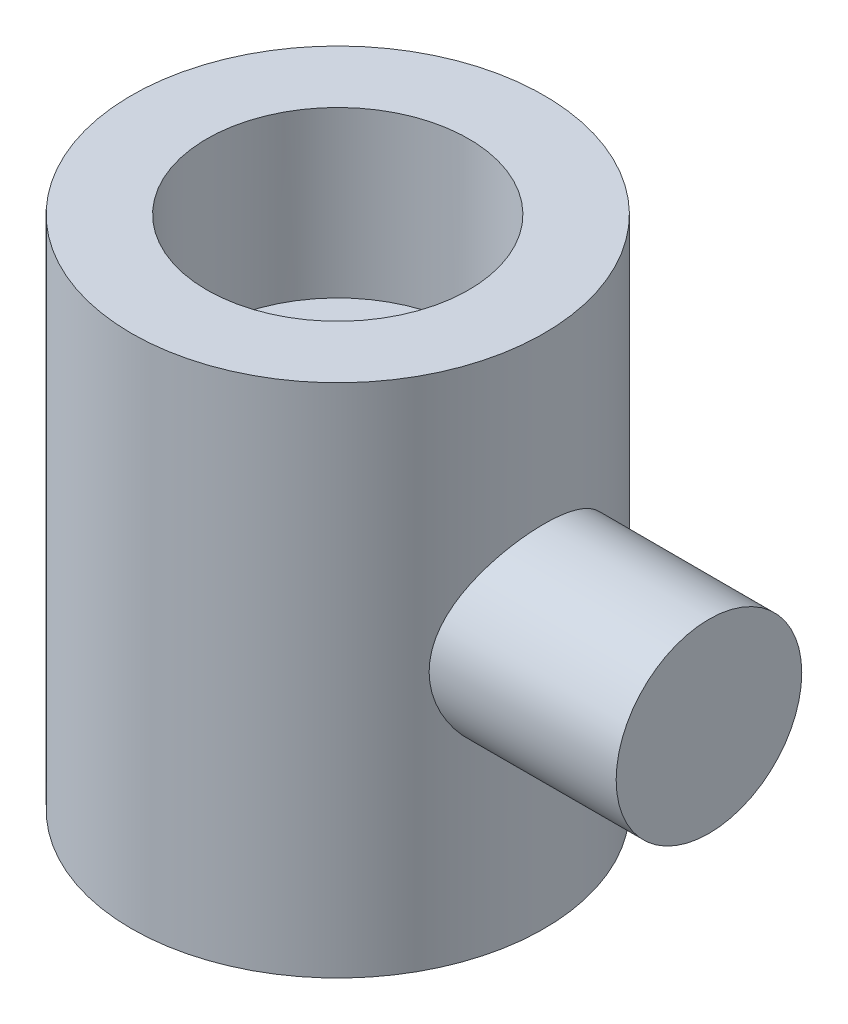
SolidWorks part; units mm, degrees
ref_plane "Front Plane" through (0, 0, 0) normal (0, 0, 1) x (1, 0, 0)
ref_plane "Top Plane" through (0, 0, 0) normal (0, 1, 0) x (1, 0, 0)
ref_plane "Right Plane" through (0, 0, 0) normal (1, 0, 0) x (0, 0, -1)
sketch "Sketch2" plane through (0, 0, 0) normal (0, 1, 0) x (1, 0, 0)
  circle A1 centre (0, 0) radius 10
  dimension "D2" = 20
extrude "Boss-Extrude1" add sketch "Sketch2" along normal blind 25
sketch "Sketch3" plane through (0, 0, 0) normal (1, 0, 0) x (0, 0, -1)
  line L0 (10, 25) -> (-10, 25) construction
  circle A1 centre (0, 12.5) radius 4.5
  point P1 (0, 11.7194)
  point P3 (0, 9.2586)
  point P4 (0, 10.5176)
  dimension "D1" = 12.5
  dimension "D2" = 9
extrude "Boss-Extrude2" add sketch "Sketch3" along normal blind 18
sketch "Sketch7" plane through (0, 25, 0) normal (0, 1, 0) x (1, 0, 0)
  circle A0 centre (0, 0) radius 6.35
  dimension "D1" = 12.7
extrude "Cut-Extrude2" cut sketch "Sketch7" against normal through all
sketch "Sketch8" plane through (0, 0, 0) normal (0, 0, 1) x (1, 0, 0)
  line L0 (-10, 0) -> (10, 0) construction
  line L1 (-7.5, 17) -> (7.5, 17)
  line L2 (-7.5, 17) -> (-7.5, 8)
  line L3 (-7.5, 8) -> (7.5, 8)
  line L4 (7.5, 17) -> (7.5, 8)
  line L5 (6.35, 25) -> (-6.35, 25) construction
  point P4 (0, 8)
  point P10 (-10, 12)
  point P11 (-8.8108, 8)
  dimension "D1" = 8
  dimension "D2" = 8
  dimension "D3" = 15
extrude "Boss-Extrude3" add sketch "Sketch8" along normal mid plane 13
